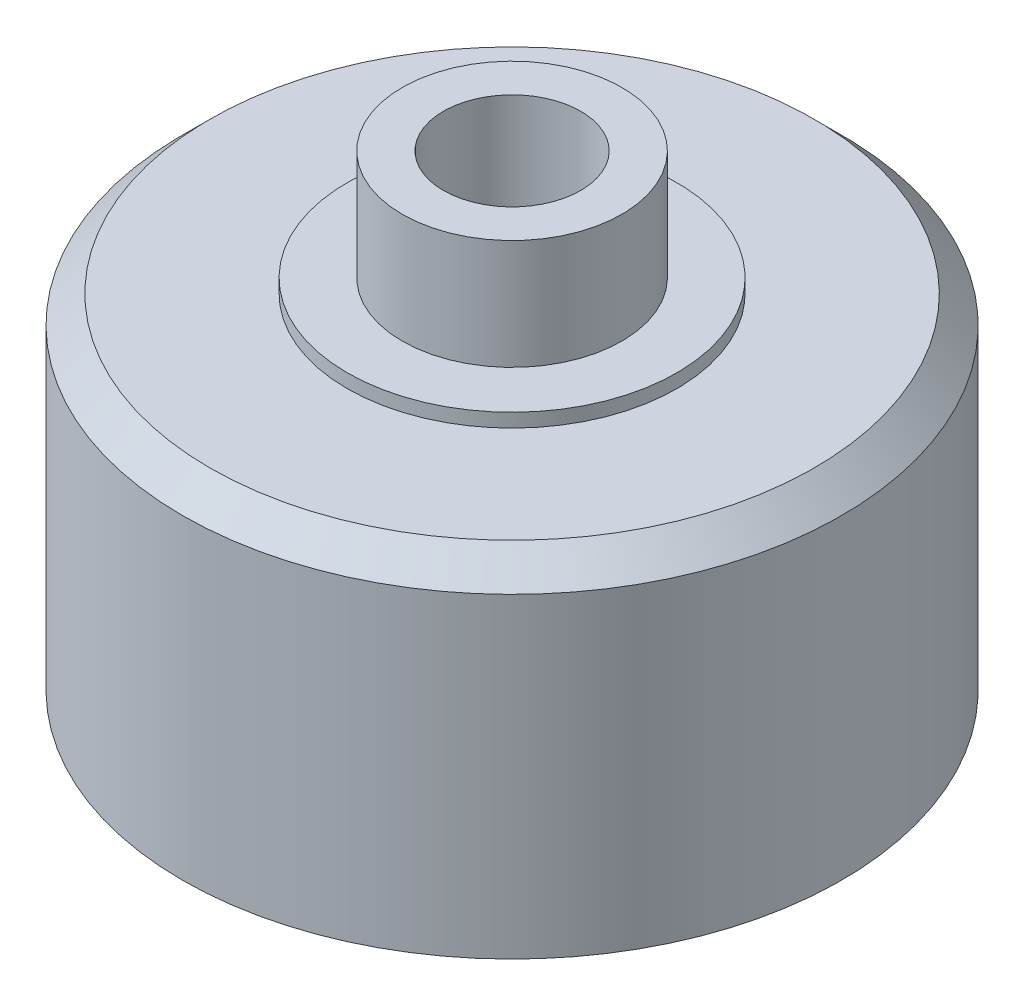
SolidWorks part; units mm, degrees
material "PBT General Purpose"
ref_plane "Front" through (0, 0, 0) normal (0, 0, 1) x (1, 0, 0)
ref_plane "Top" through (0, 0, 0) normal (0, 1, 0) x (1, 0, 0)
ref_plane "Right" through (0, 0, 0) normal (1, 0, 0) x (0, 0, -1)
sketch "Sketch1" plane through (0, 0, 0) normal (0, 1, 0) x (1, 0, 0)
  circle A0 centre (0, 0) radius 12
  dimension "D1" = 24
extrude "Boss-Extrude1" add sketch "Sketch1" along normal blind 12.5
sketch "Sketch2" plane through (0, 12.5, 0) normal (0, 1, 0) x (1, 0, 0)
  circle A0 centre (0, 0) radius 4
  dimension "D1" = 8
extrude "Boss-Extrude2" add sketch "Sketch2" along normal blind 4.5
shell "Shell1" thickness 1.5
chamfer "Chamfer2" distance 1 angle 45 1 edges at (0, 12.5, 12)
sketch "Sketch3" plane through (0, 12.5, 0) normal (0, 1, 0) x (1, 0, 0)
  circle A0 centre (0, 0) radius 6
  circle A1 centre (0, 0) radius 4
  dimension "D1" = 12
extrude "Boss-Extrude3" add sketch "Sketch3" along normal blind 0.5 contours A1
sketch "Sketch4" plane through (0, 0, 0) normal (0, 1, 0) x (1, 0, 0)
  line L0 (0, -12) -> (0, 12) construction
  line L1 (-2.5, -10.198) -> (-2.5, -8.3923)
  line L2 (-2.5, -8.3923) -> (-1.5, -8.3923)
  line L3 (-1.5, -8.3923) -> (-1.5, -10.3923)
  circle A0 centre (0, 0) radius 12 construction
  circle A1 centre (0, 0) radius 10.5 construction
  circle A2 centre (0, 0) radius 10.5 construction
  arc A3 (-1.5, -10.3923) -> (-2.5, -10.198) centre (0, 0) cw
  dimension "D1" = 1
  dimension "D2" = 1.5
  dimension "D3" = 2
extrude "Boss-Extrude4" add sketch "Sketch4" along normal up to surface (11 mm away) up to face at (0, 11, 2.5)
mirror "Mirror1" about plane through (0, 0, 0) normal (1, 0, 0) of "Boss-Extrude4"
mirror "Mirror2" about plane through (0, 0, 0) normal (0, 0, 1) of "Mirror1", "Boss-Extrude4"
sketch "Sketch5" plane through (0, 0, 0) normal (0, 1, 0) x (1, 0, 0)
  line L1 (-8.25, 6.4952) -> (8.25, 6.4952) construction
  line L2 (-8.25, 6.4952) -> (-8.25, -6.4952) construction
  line L3 (-8.25, -6.4952) -> (8.25, -6.4952) construction
  line L4 (8.25, 6.4952) -> (8.25, -6.4952) construction
  line L5 (-8.25, 6.4952) -> (8.25, -6.4952) construction
  line L6 (-8.25, -6.4952) -> (8.25, 6.4952) construction
  arc A0 (2.5, -10.198) -> (2.5, 10.198) centre (0, 0) ccw construction
  circle A1 centre (-8.25, -6.4952) radius 1.5
  point P0 (0, 0)
  dimension "D2" = 3
  dimension "D1" = 16.5
extrude "Boss-Extrude5" add sketch "Sketch5" along normal up to surface (11 mm away) up to face at (0, 11, 2.5)
mirror "Mirror3" about plane through (0, 0, 0) normal (1, 0, 0) of "Boss-Extrude5"
mirror "Mirror4" about plane through (0, 0, 0) normal (0, 0, 1) of "Mirror3", "Boss-Extrude5"
sketch "Sketch6" plane through (0, 0, 0) normal (0, 1, 0) x (1, 0, 0)
  line L1 (-8.25, 6.4952) -> (8.25, 6.4952) construction
  line L2 (-8.25, 6.4952) -> (-8.25, -6.4952) construction
  line L3 (-8.25, -6.4952) -> (8.25, -6.4952) construction
  line L4 (8.25, 6.4952) -> (8.25, -6.4952) construction
  line L5 (-8.25, 6.4952) -> (8.25, -6.4952) construction
  line L6 (-8.25, -6.4952) -> (8.25, 6.4952) construction
  arc A0 (9.0913, -5.2534) -> (9.0913, 5.2534) centre (0, 0) ccw construction
  circle A1 centre (-8.25, -6.4952) radius 0.75
  point P0 (0, 0)
  dimension "D2" = 1.5
  dimension "D1" = 16.5
extrude "Cut-Extrude1" cut sketch "Sketch6" along normal blind 8
cosmetic thread "Cosmetic Thread1" parameters "D2"=2
mirror "Mirror5" about plane through (0, 0, 0) normal (1, 0, 0) of "Cut-Extrude1"
mirror "Mirror6" about plane through (0, 0, 0) normal (0, 0, 1) of "Mirror5", "Cut-Extrude1"
